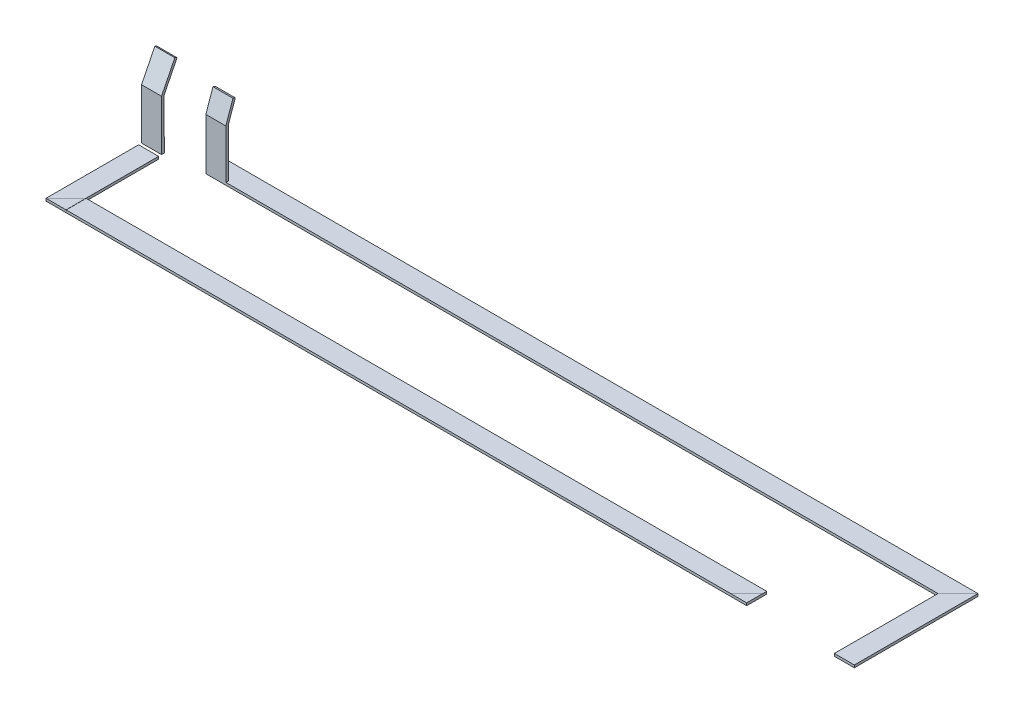
SolidWorks part; units mm, degrees
ref_plane "Alzado" through (0, 0, 0) normal (0, 0, 1) x (1, 0, 0)
ref_plane "Planta" through (0, 0, 0) normal (0, 1, 0) x (1, 0, 0)
ref_plane "Vista lateral" through (0, 0, 0) normal (1, 0, 0) x (0, 0, -1)
sketch "Croquis2" plane through (0, 0, 0) normal (0, 1, 0) x (1, 0, 0)
  line L1 (-25.4, 3.155) -> (25.4, 3.155)
  line L2 (-25.4, 3.155) -> (-25.4, -3.155)
  line L3 (-25.4, -3.155) -> (25.4, -3.155)
  line L4 (25.4, 3.155) -> (25.4, -3.155)
  line L5 (-25.4, 3.155) -> (25.4, -3.155) construction
  line L6 (-25.4, -3.155) -> (25.4, 3.155) construction
  line L7 (238.1, 3.155) -> (288.9, 3.155)
  line L8 (238.1, 3.155) -> (238.1, -3.155)
  line L9 (238.1, -3.155) -> (288.9, -3.155)
  line L10 (288.9, 3.155) -> (288.9, -3.155)
  line L11 (238.1, 3.155) -> (288.9, -3.155) construction
  line L12 (238.1, -3.155) -> (288.9, 3.155) construction
  point P0 (0, 0)
  point P6 (263.5, 0)
  dimension "D1" = 50.8
  dimension "D2" = 6.31
  dimension "D3" = 263.5
  dimension "D4" = 50.8
  dimension "D5" = 6.31
sketch3d "Croquis3D1"
  line L0 (0, 0, 0) -> (0, -567.24, 0)
  line L1 (0, -567.24, 0) -> (0, -567.24, 316.2)
  line L2 (0, -567.24, 316.2) -> (1786.7, -567.24, 316.2)
  line L3 (1786.7, -567.24, 316.2) -> (1786.7, -567.24, 578)
  line L4 (-25.4, 0, 0) -> (-25.4, -383.9185, 0) construction
  line L5 (-25.4, 0, -3.155) -> (-25.4, 0, 3.155) construction
  line L6 (-25.4, -383.9185, 0) -> (-25.4, -383.9185, 653.2834) construction
  line L7 (1786.7, -567.24, 578) -> (1786.7, -435.4728, 578)
  line L8 (1786.7, -435.4728, 578) -> (1786.7, -435.4728, 1432.0029)
  dimension "D1" = 567.24
  dimension "D2" = 316.2
  dimension "D3" = 1786.7
  dimension "D4" = 261.8
  dimension "D5" = 131.7672
  dimension "D6" = 854.0029
sweep "Barrer1" add profiles "Croquis2" path "Croquis3D1"
sketch "Croquis3" plane through (0, 0, -3.155) normal (0, 0, -1) x (-1, 0, 0)
  line L0 (-288.9, 0) -> (-288.9, -6.31)
  line L1 (-288.9, 0) -> (-288.9, -570.395) construction
  line L2 (-288.9, -6.31) -> (-238.1, -6.31)
  line L3 (-238.1, 0) -> (-238.1, -570.395) construction
  line L4 (-238.1, -6.31) -> (-238.1, 0)
  line L5 (-238.1, 0) -> (-288.9, 0)
  line L7 (-25.4, 0) -> (-25.4, -6.31)
  line L8 (-25.4, 0) -> (-25.4, -570.395) construction
  line L9 (-25.4, -6.31) -> (25.4, -6.31)
  line L10 (25.4, 0) -> (25.4, -570.395) construction
  line L11 (25.4, -6.31) -> (25.4, 0)
  line L12 (-25.4, 0) -> (25.4, 0) construction
  line L13 (25.4, 0) -> (-25.4, 0)
  dimension "D1" = 6.31
  dimension "D2" = 6.31
sketch3d "Croquis3D2"
  line L0 (25.4, -3.155, -3.155) -> (-0.201, -3.155, -3.155) construction
  line L1 (25.4, 0, -3.155) -> (25.4, -6.31, -3.155) construction
  line L2 (-0.201, -3.155, -3.155) -> (-0.201, -5.2746, -3.155) construction
  line L3 (-0.201, -3.155, -3.155) -> (-0.201, -3.155, -207.155)
  line L4 (-0.201, -3.155, -207.155) -> (-0.201, -53.155, -207.155)
  dimension "D1" = 204
  dimension "D2" = 50
sweep "Barrer4" add profiles "Croquis3" path "Croquis3D2"
sketch "Croquis4" plane through (0, 0, -210.31) normal (0, 0, -1) x (-1, 0, 0)
  line L0 (-238.1, 0) -> (-238.1, -53.155)
  line L1 (-238.1, -53.155) -> (-178.1, -53.155)
  line L2 (-178.1, -53.155) -> (-178.1, 0)
  line L3 (-178.1, 0) -> (-238.1, 0)
  dimension "D1" = 60
extrude "Saliente-Extruir1" add sketch "Croquis4" against normal blind 6.31
sketch "Croquis5" plane through (0, 0, -204) normal (0, 0, 1) x (1, 0, 0)
  line L0 (238.1, -6.31) -> (178.1, -6.31)
  line L1 (178.1, -53.155) -> (178.1, 0) construction
  line L2 (178.1, -6.31) -> (178.1, 0)
  line L3 (178.1, 0) -> (238.1, 0)
  line L4 (238.1, 0) -> (238.1, -6.31)
extrude "Cortar-Extruir1" cut sketch "Croquis5" against normal blind 6.31
sketch "Croquis6" plane through (0, -432.3178, 0) normal (0, 1, 0) x (1, 0, 0)
  circle A0 centre (1285.7, -1260.295) radius 4.75
  circle A1 centre (1495.7, -1260.295) radius 4.75
sketch "Croquis7" plane through (0, 0, 3.155) normal (0, 0, 1) x (1, 0, 0)
  line L0 (288.9, -564.085) -> (238.1, -564.085)
  line L1 (238.1, -564.085) -> (238.1, -68.8755)
  line L2 (238.1, 0) -> (238.1, -564.085) construction
  line L3 (238.1, -68.8755) -> (170.6111, -68.8755)
  line L4 (170.6111, -68.8755) -> (170.6111, 0)
  line L5 (170.6111, 0) -> (288.9, 0)
  line L6 (288.9, 0) -> (288.9, -564.085)
extrude "Cortar-Extruir2" cut sketch "Croquis7" against normal blind 502
sketch "Croquis8" plane through (0, 0, 3.155) normal (0, 0, 1) x (1, 0, 0)
  line L0 (25.4, -564.085) -> (-25.4, -564.085)
  line L1 (-25.4, -564.085) -> (-25.4, 0)
  line L2 (-25.4, 0) -> (25.4, 0)
  line L3 (25.4, 0) -> (25.4, -564.085)
extrude "Cortar-Extruir3" cut sketch "Croquis8" against normal blind 502
sketch "Croquis9" plane through (0, -432.3178, 0) normal (0, 1, 0) x (1, 0, 0)
  line L0 (1761.3, -341.6) -> (2075.6, -341.6)
  line L1 (2075.6, -27.3) -> (2075.6, -574.845) construction
  line L2 (2075.6, -341.6) -> (2075.6, -1432.0029)
  line L3 (2075.6, -1432.0029) -> (1761.3, -1432.0029)
  line L4 (1761.3, -341.6) -> (1761.3, -1432.0029)
extrude "Cortar-Extruir4" cut sketch "Croquis9" against normal blind 502
sketch "Croquis10" plane through (0, 0, -3.155) normal (0, 0, -1) x (-1, 0, 0)
  line L0 (-25.4, -564.085) -> (25.4, -564.085)
  line L1 (25.4, -564.085) -> (25.4, -570.395)
  line L2 (25.4, -570.395) -> (-25.4, -570.395)
  line L3 (-25.4, -570.395) -> (-25.4, -564.085)
extrude "Cortar-Extruir5" cut sketch "Croquis10" against normal blind 95
sketch "Croquis11" plane through (0, -564.085, 0) normal (0, 1, 0) x (1, 0, 0)
  line L0 (288.9, -27.3) -> (238.1, -27.3)
  line L1 (238.1, -3.155) -> (238.1, -78.1) construction
  line L2 (238.1, -78.1) -> (288.9, -78.1)
  line L3 (238.1, -78.1) -> (2024.8, -78.1) construction
  line L4 (288.9, -78.1) -> (288.9, -27.3)
  line L5 (288.9, -27.3) -> (288.9, 3.155)
  line L6 (288.9, 3.155) -> (238.1, 3.155)
  line L7 (238.1, 3.155) -> (238.1, -27.3)
  line M1 (288.9, -27.3) -> (288.9, -3.155)
  line M2 (288.9, -3.155) -> (288.9, 3.155)
  line M3 (288.9, 3.155) -> (238.1, 3.155)
  line M4 (238.1, 3.155) -> (238.1, -3.155)
  line M5 (238.1, -3.155) -> (238.1, -78.1)
  line M6 (238.1, -78.1) -> (288.9, -27.3)
extrude "Cortar-Extruir6" cut sketch "Croquis11" against normal blind 95 contours L2 L4 M6 | L0 M6 M5 | L0 M1 M2 M3 M4 M5
sketch "Croquis13" plane through (0, -564.085, 0) normal (0, 1, 0) x (1, 0, 0)
  line L0 (-25.4, -91.845) -> (-25.4, -341.6)
  line L1 (-25.4, -341.6) -> (94.6, -341.6)
  line L2 (-25.4, -341.6) -> (1761.3, -341.6) construction
  line L3 (94.6, -341.6) -> (94.6, -91.845)
  line L4 (94.6, -91.845) -> (-25.4, -91.845)
  dimension "D1" = 120
extrude "Cortar-Extruir7" cut sketch "Croquis13" against normal blind 95
sketch "Croquis16" plane through (0, -564.085, 0) normal (0, 1, 0) x (1, 0, 0)
  line L2 (288.9, -27.3) -> (163.9, -27.3)
  line L3 (163.9, -27.3) -> (163.9, -78.1)
  line L4 (163.9, -78.1) -> (288.9, -78.1)
  line L5 (288.9, -27.3) -> (288.9, -78.1)
  dimension "D1" = 125
extrude "Saliente-Extruir4" add sketch "Croquis16" against normal blind 6.31
sketch "Croquis17" plane through (94.6, 0, 0) normal (-1, 0, 0) x (0, 0, 1)
  line L0 (290.8, -564.085) -> (290.8, -570.395)
  line L1 (290.8, -570.395) -> (341.6, -570.395)
  line L2 (341.6, -570.395) -> (341.6, -564.085)
  line L3 (341.6, -564.085) -> (290.8, -564.085)
  line L4 (316.2, -564.085) -> (316.2, -570.395) construction
  line L5 (316.2, -570.395) -> (316.2, -567.24) construction
  line L6 (316.2, -567.24) -> (341.6, -567.24) construction
sketch3d "Croquis3D3"
  line L0 (94.6, -567.24, 316.2) -> (46.55, -567.24, 316.2)
  line L1 (46.55, -567.24, 316.2) -> (46.55, -567.24, 106.2)
  dimension "D1" = 48.05
  dimension "D2" = 210
sweep "Barrer5" add profiles "Croquis17" path "Croquis3D3"
sketch "Croquis18" plane through (21.15, 0, 0) normal (-1, 0, 0) x (0, 0, 1)
  line L0 (98.7872, -564.085) -> (98.7872, -435.523)
  line L1 (341.6, -564.085) -> (106.2, -564.085) construction
  line L2 (98.7872, -435.523) -> (64.97, -367.6227)
  line L3 (64.97, -367.6227) -> (59.3217, -370.4358)
  line L4 (59.3217, -370.4358) -> (91.8975, -435.8435)
  line L5 (91.8975, -435.8435) -> (91.8429, -564.085)
  line L6 (91.8429, -564.085) -> (98.7872, -564.085)
  dimension "D1" = 6.31
extrude "Saliente-Extruir5" add sketch "Croquis18" against normal blind 50.8
sketch "Croquis20" plane through (163.9, 0, 0) normal (-1, 0, 0) x (0, 0, 1)
  line L0 (78.1, -564.085) -> (78.1, -439.8845)
  line L1 (78.1, -439.8845) -> (59.9661, -387.9255)
  line L2 (59.9661, -387.9255) -> (54.0085, -390.0047)
  line L3 (54.0085, -390.0047) -> (71.79, -440.954)
  line L4 (71.79, -440.954) -> (71.79, -564.085)
  line L5 (27.3, -564.085) -> (78.1, -564.085) construction
  line L6 (71.79, -564.085) -> (78.1, -564.085)
  dimension "D1" = 6.31
  dimension "D2" = 6.31
extrude "Saliente-Extruir6" add sketch "Croquis20" against normal blind 50.8
sketch "Croquis21" plane through (0, -564.085, 0) normal (0, 1, 0) x (1, 0, 0)
  line L0 (1812.1, -290.8) -> (1802.1, -290.8)
  line L1 (71.95, -290.8) -> (1812.1, -290.8) construction
  line L2 (1802.1, -290.8) -> (1802.1, -341.6)
  line L3 (1761.3, -341.6) -> (1812.1, -341.6) construction
  line L4 (1802.1, -341.6) -> (1812.1, -341.6)
  line L5 (1812.1, -341.6) -> (1812.1, -290.8)
  dimension "D1" = 10
extrude "Cortar-Extruir9" cut sketch "Croquis21" against normal blind 53
sketch "Croquis22" plane through (0, -564.085, 0) normal (0, 1, 0) x (1, 0, 0)
  line L1 (71.95, -290.8) -> (71.95, -341.6)
  line L2 (21.15, -341.6) -> (1761.3, -341.6) construction
  line L3 (71.95, -341.6) -> (72.45, -341.6)
  line L4 (72.45, -341.6) -> (72.45, -290.8)
  line L5 (71.95, -290.8) -> (1802.1, -290.8) construction
  line L6 (72.45, -290.8) -> (71.95, -290.8)
  dimension "D1" = 0.5
extrude "Cortar-Extruir10" cut sketch "Croquis22" against normal blind 10
sketch "Croquis23" plane through (0, -570.395, 0) normal (0, -1, 0) x (1, 0, 0)
  line L0 (2024.8, 341.6) -> (2024.8, 78.1)
